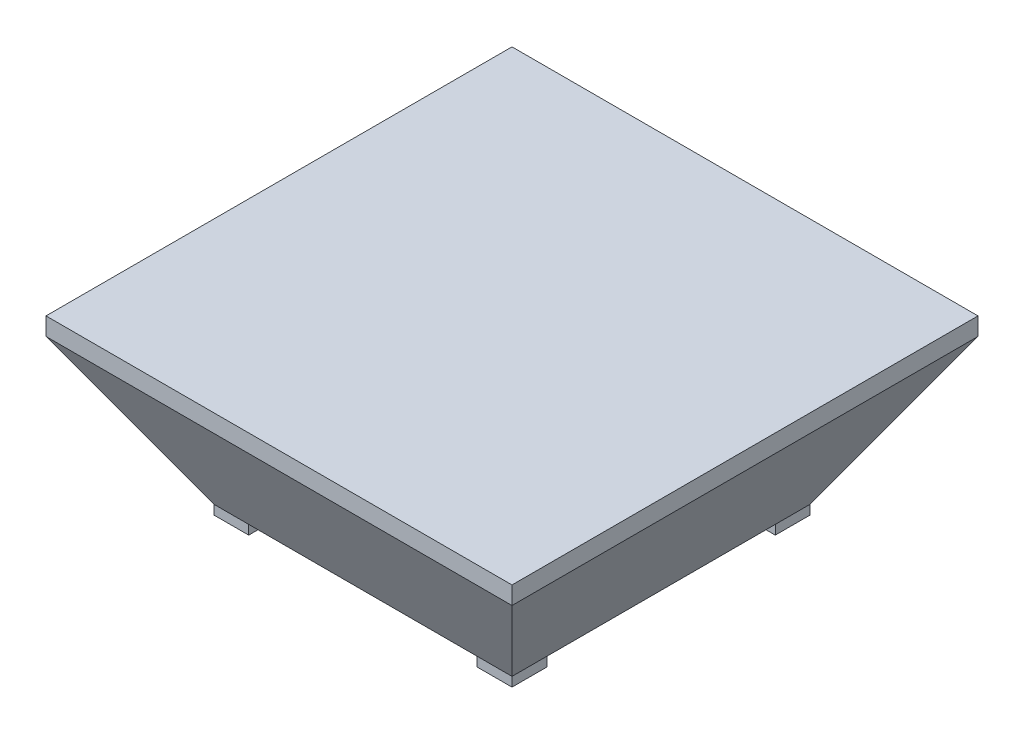
SolidWorks part; units mm, degrees
material "Caoba"
ref_plane "Alzado" through (0, 0, 0) normal (0, 0, 1) x (1, 0, 0)
ref_plane "Planta" through (0, 0, 0) normal (0, 1, 0) x (1, 0, 0)
ref_plane "Vista lateral" through (0, 0, 0) normal (1, 0, 0) x (0, 0, -1)
sketch "Croquis1" plane through (0, 0, 0) normal (0, 1, 0) x (1, 0, 0)
  line L1 (500, -500) -> (-500, -500)
  line L2 (500, -500) -> (500, 500)
  line L3 (500, 500) -> (-500, 500)
  line L4 (-500, -500) -> (-500, 500)
  line L5 (500, -500) -> (-500, 500) construction
  line L6 (500, 500) -> (-500, -500) construction
  point P0 (0, 0)
  dimension "D1" = 1000
  dimension "D2" = 1000
extrude "Saliente-Extruir1" add sketch "Croquis1" along normal blind 350
chamfer "Chaflán1" distance 180 angle 60 4 edges at (-500, 0, 0) (0, 0, -500) (500, 0, 0) (0, 0, 500)
sketch "Croquis2" plane through (0, 0, 0) normal (0, -1, 0) x (1, 0, 0)
  line L0 (0, 320) -> (0, -320) construction
  line L1 (-245, 245) -> (-320, 245)
  line L2 (-245, 245) -> (-245, 320)
  line L3 (-245, 320) -> (-320, 320)
  line L4 (-320, 245) -> (-320, 320)
  line L5 (-245, 245) -> (-320, 320) construction
  line L6 (-245, 320) -> (-320, 245) construction
  line L7 (320, 320) -> (-320, 320) construction
  line L8 (-320, -320) -> (320, -320) construction
  line L9 (-320, 0) -> (320, 0) construction
  line L10 (-320, 320) -> (-320, -320) construction
  line L11 (320, -320) -> (320, 320) construction
  line L12 (320, 245) -> (320, 320)
  line L13 (245, 320) -> (320, 320)
  line L14 (245, 320) -> (320, 245) construction
  line L15 (245, 245) -> (320, 320) construction
  line L16 (245, 245) -> (245, 320)
  line L17 (245, 245) -> (320, 245)
  line L18 (245, -245) -> (320, -320) construction
  line L19 (245, -320) -> (320, -245) construction
  line L20 (-245, -320) -> (-320, -245) construction
  line L21 (-245, -245) -> (-320, -320) construction
  line L22 (245, -245) -> (320, -245)
  line L23 (245, -245) -> (245, -320)
  line L24 (245, -320) -> (320, -320)
  line L25 (320, -245) -> (320, -320)
  line L26 (-320, -245) -> (-320, -320)
  line L27 (-245, -320) -> (-320, -320)
  line L28 (-245, -245) -> (-245, -320)
  line L29 (-245, -245) -> (-320, -245)
  point P0 (-282.5, 282.5)
  point P22 (282.5, 282.5)
  point P31 (282.5, -282.5)
  point P32 (-282.5, -282.5)
  dimension "D1" = 75
  dimension "D2" = 75
extrude "Saliente-Extruir2" add sketch "Croquis2" along normal blind 20
